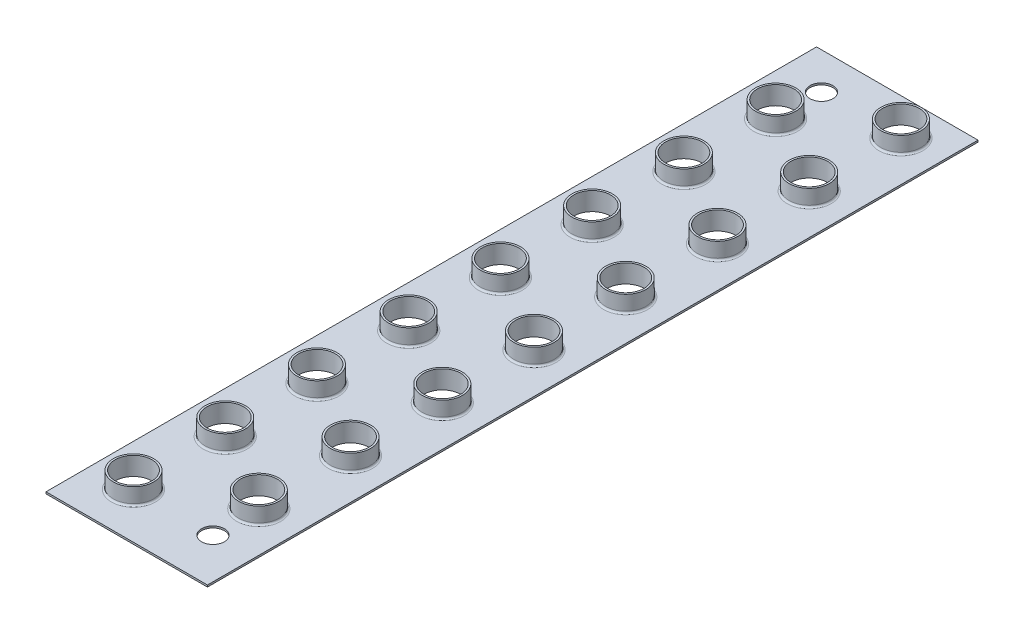
SolidWorks part; units mm, degrees
material "Alloy Steel"
ref_plane "Front Plane" through (0, 0, 0) normal (0, 0, 1) x (1, 0, 0)
ref_plane "Top Plane" through (0, 0, 0) normal (0, 1, 0) x (1, 0, 0)
ref_plane "Right Plane" through (0, 0, 0) normal (1, 0, 0) x (0, 0, -1)
sketch "Sketch1" plane through (0, 0, 0) normal (0, 1, 0) x (1, 0, 0)
  line L1 (0, 0) -> (44, 0)
  line L2 (0, 0) -> (0, 210)
  line L3 (0, 210) -> (44, 210)
  line L4 (44, 0) -> (44, 210)
  dimension "D1" = 210
  dimension "D2" = 44
extrude "Boss-Extrude1" add sketch "Sketch1" along normal blind 0.5
sketch "Sketch2" plane through (0, 0.5, 0) normal (0, 1, 0) x (1, 0, 0)
  line L0 (44, 210) -> (0, 210) construction
  line L1 (44, 0) -> (44, 210) construction
  circle A0 centre (33, 200) radius 5
  circle A1 centre (11.3494, 187.5) radius 5
  dimension "D1" = 10
  dimension "D2" = 10
  dimension "D3" = 10
  dimension "D4" = 12.5
  dimension "D5" = 25
  dimension "D6" = 11
extrude "Cut-Extrude1" cut sketch "Sketch2" against normal blind 0.5
sketch "Sketch3" plane through (0, 0.5, 0) normal (0, 1, 0) x (1, 0, 0)
  circle A14 centre (11.3494, 187.5) radius 5.5
  circle A15 centre (11.3494, 187.5) radius 5.5
  circle A17 centre (33, 200) radius 5.5
  circle A18 centre (33, 200) radius 5.5
  circle M3 centre (33, 200) radius 5
  circle M4 centre (11.3494, 187.5) radius 5
  dimension "D1" = 0.5
  dimension "D2" = 0.5
extrude "Boss-Extrude3" add sketch "Sketch3" along normal blind 4.5 contours A18 M3 | A15 M4
fillet "Fillet1" radius 0.5 2 edges at (33, 0.5, -205.5) (11.3494, 0.5, -193)
pattern_linear "LPattern1" count 8 spacing 25 along (0, 0, 1) of "Boss-Extrude3", "Cut-Extrude1", "Fillet1"
sketch "Sketch5" plane through (0, 0.5, 0) normal (0, 1, 0) x (1, 0, 0)
  line L0 (11.3494, 12.5) -> (33, 12.5) construction
  line L1 (33, 12.5) -> (33, 25) construction
  line L2 (33, 200) -> (11.3494, 200) construction
  line L3 (11.3494, 200) -> (11.3494, 187.5) construction
  circle A0 centre (33, 12.5) radius 3.1
  circle A1 centre (11.3494, 200) radius 3.1
  dimension "D1" = 6.2
  dimension "D2" = 6.2
extrude "Cut-Extrude2" cut sketch "Sketch5" against normal blind 4.5
